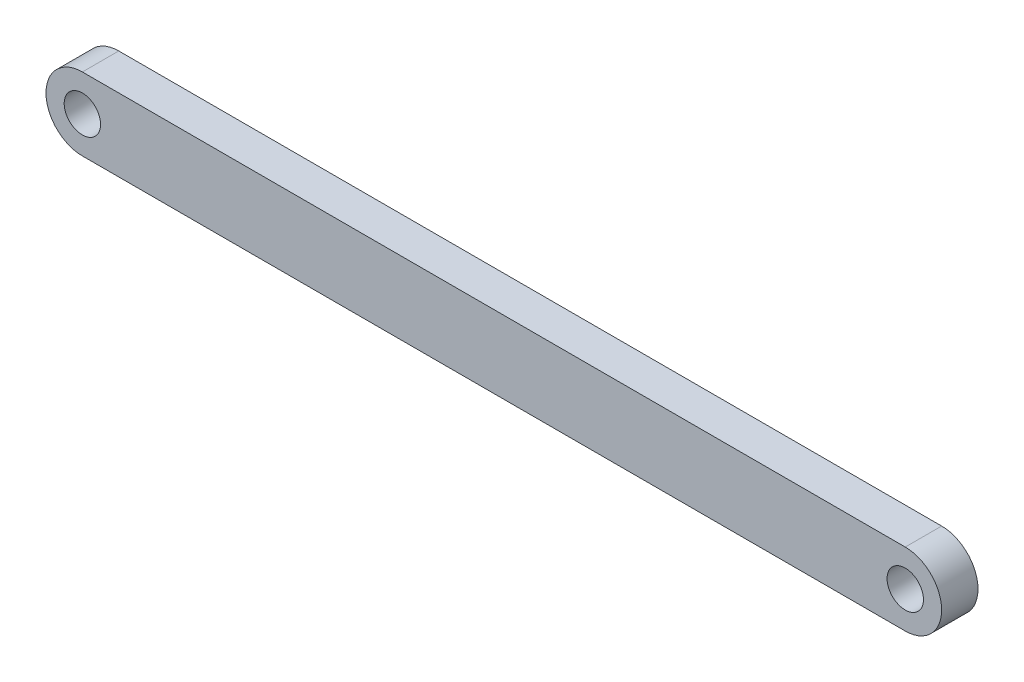
SolidWorks part; units mm, degrees
ref_plane "Plano frontal" through (0, 0, 0) normal (0, 0, 1) x (1, 0, 0)
ref_plane "Plano superior" through (0, 0, 0) normal (0, 1, 0) x (1, 0, 0)
ref_plane "Plano direito" through (0, 0, 0) normal (1, 0, 0) x (0, 0, -1)
sketch "Esboço1" plane through (0, 0, 0) normal (0, 0, 1) x (1, 0, 0)
  line L0 (-56.55, 5) -> (56.55, 5)
  line L1 (-15.7264, 0) -> (15.7264, 0) construction
  line L2 (-56.55, -5) -> (56.55, -5)
  arc A0 (-56.55, 5) -> (-56.55, -5) centre (-56.55, 0) ccw
  arc A1 (56.55, 5) -> (56.55, -5) centre (56.55, 0) cw
  circle A4 centre (-56.55, 0) radius 2.5
  circle A5 centre (56.55, 0) radius 2.5
  point P3 (0, 5)
  dimension "D2" = 113.1
  dimension "D3" = 5
  dimension "D4" = 5
  dimension "D1" = 5
extrude "Ressalto-extrusão1" add sketch "Esboço1" along normal blind 5
